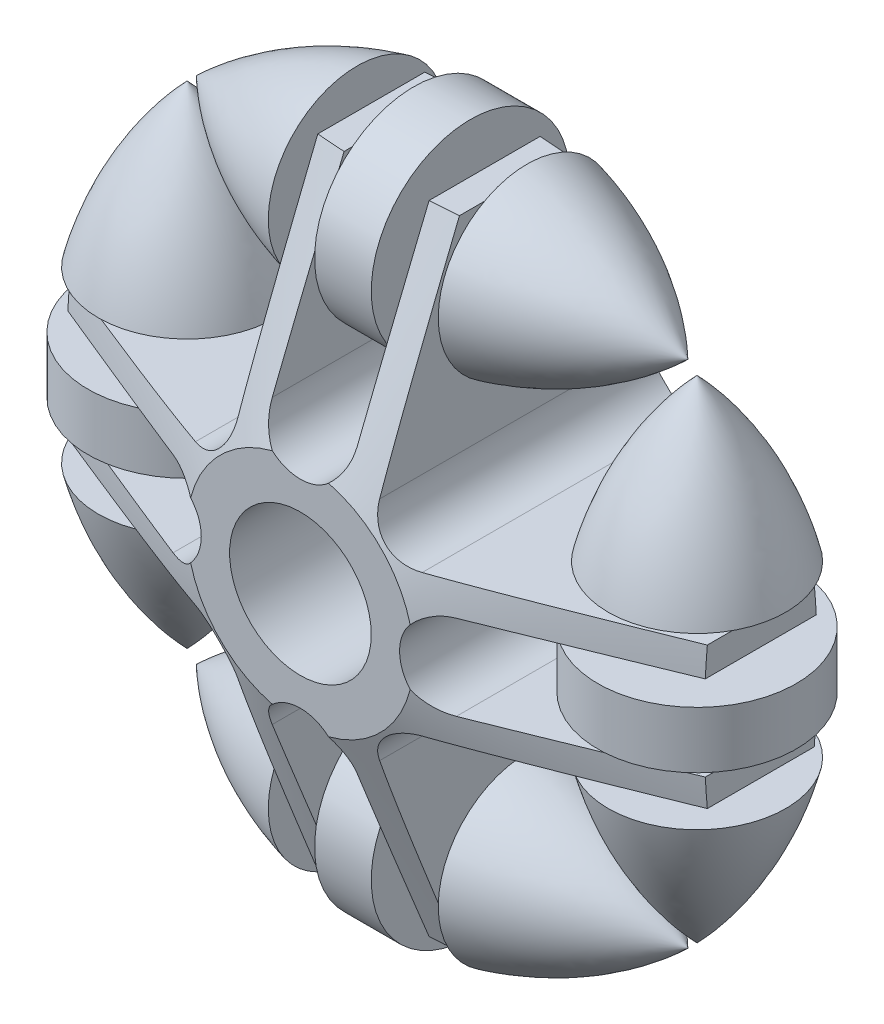
SolidWorks part; units mm, degrees
ref_plane "前视基准面" through (0, 0, 0) normal (0, 0, 1) x (1, 0, 0)
ref_plane "上视基准面" through (0, 0, 0) normal (0, 1, 0) x (1, 0, 0)
ref_plane "右视基准面" through (0, 0, 0) normal (1, 0, 0) x (0, 0, -1)
sketch "草图1" plane through (0, 0, 0) normal (0, 0, 1) x (1, 0, 0)
  line L0 (0, 0) -> (69.8665, 0) construction
  line L1 (0, 0) -> (0, 58.0263) construction
  line L2 (-5, 22.5) -> (-3, 22.5)
  line L3 (-5, 8) -> (-5, 22.5)
  line L4 (-3, 10) -> (-3, 22.5)
  line L5 (3, 22.5) -> (5, 22.5)
  line L6 (3, 10) -> (3, 22.5)
  line L7 (5, 8) -> (5, 22.5)
  line L8 (22.5, 5) -> (22.5, 3)
  line L9 (10, 3) -> (22.5, 3)
  line L10 (22.5, -3) -> (22.5, -5)
  line L11 (10, -3) -> (22.5, -3)
  line L12 (8, 5) -> (22.5, 5)
  line L13 (8, -5) -> (22.5, -5)
  line L14 (5, -22.5) -> (3, -22.5)
  line L15 (3, -10) -> (3, -22.5)
  line L16 (-3, -22.5) -> (-5, -22.5)
  line L17 (-3, -10) -> (-3, -22.5)
  line L18 (5, -8) -> (5, -22.5)
  line L19 (-5, -8) -> (-5, -22.5)
  line L20 (-22.5, -5) -> (-22.5, -3)
  line L21 (-10, -3) -> (-22.5, -3)
  line L22 (-22.5, 3) -> (-22.5, 5)
  line L23 (-10, 3) -> (-22.5, 3)
  line L24 (-8, -5) -> (-22.5, -5)
  line L25 (-8, 5) -> (-22.5, 5)
  circle A0 centre (0, 0) radius 5
  arc A1 (-3, 10) -> (3, 10) centre (0, 10) ccw
  arc A2 (10, 3) -> (10, -3) centre (10, 0) ccw
  arc A3 (3, -10) -> (-3, -10) centre (0, -10) ccw
  arc A4 (-10, -3) -> (-10, 3) centre (-10, 0) ccw
  arc A5 (-5, -8) -> (-8, -5) centre (-8, -8) ccw
  arc A6 (5, -8) -> (8, -5) centre (8, -8) cw
  arc A7 (8, 5) -> (5, 8) centre (8, 8) cw
  arc A8 (-8, 5) -> (-5, 8) centre (-8, 8) ccw
  point P11 (0, 7)
  point P12 (0, 5)
  point P24 (7, 0)
  point P34 (0, -7)
  point P44 (-7, 0)
  dimension "D1" = 10
  dimension "D2" = 6
  dimension "D6" = 3
  dimension "D3" = 22.5
  dimension "D4" = 2
  dimension "D5" = 4
extrude "凸台-拉伸1" add sketch "草图1" along normal mid plane 20
sketch "草图2" plane through (0, 0, 0) normal (1, 0, 0) x (0, 0, -1)
  line L0 (0, 0) -> (0, 26.2614) construction
  line L1 (-10, 8) -> (-10, 24.3673)
  line L2 (-10, 24.3673) -> (-3.2273, 24.3673)
  line L3 (-3.2273, 24.3673) -> (-10, 8)
  line L4 (-10, 22.5) -> (10, 22.5) construction
  line L5 (-10, 8) -> (10, 8) construction
  line L6 (-10, 8) -> (-10, 5) construction
  line L7 (3.2273, 24.3673) -> (10, 8)
  line L8 (10, 24.3673) -> (3.2273, 24.3673)
  line L9 (10, 8) -> (10, 24.3673)
  point P8 (-4, 22.5)
  point P18 (4, 22.5)
  dimension "D1" = 4
revolve "切除-旋转1" cut sketch "草图2" angle 360 about axis through (0, 0, 10) along (0, 0, -1)
sketch "草图3" plane through (0, 0, 0) normal (1, 0, 0) x (0, 0, -1)
  line L0 (0, 0) -> (0, 31.4796) construction
  circle A0 centre (0, 18) radius 7
  point P5 (0, 25)
  dimension "D1" = 14
  dimension "D2" = 25
extrude "凸台-拉伸2" add sketch "草图3" along normal mid plane 4 separate body
pattern_circular "阵列(圆周)1" count 4 over 360 about axis through (0, 0, 0) along (0, 0, 1) of bodies 103
sketch "草图4" plane through (0, 0, 0) normal (0, 0, 1) x (1, 0, 0)
  line L0 (2, 18) -> (27.6779, 18) construction
  line L1 (2, 11) -> (2, 25) construction
  line L2 (6, 24.2693) -> (6, 18)
  line L3 (6, 18) -> (17.3494, 18)
  arc A0 (17.3494, 18) -> (6, 24.2693) centre (0, 0) ccw
  dimension "D1" = 50
  dimension "D2" = 4
revolve "旋转1" add sketch "草图4" angle 360 about L0
pattern_circular "阵列(圆周)3" count 4 over 360 about axis through (0, 0, 0) along (0, 0, 1) of bodies 107
mirror "镜向1" about plane through (0, 0, 0) normal (1, 0, 0) of bodies 107
pattern_circular "阵列(圆周)4" count 4 over 360 about axis through (0, 0, 0) along (0, 0, 1) of bodies 111
